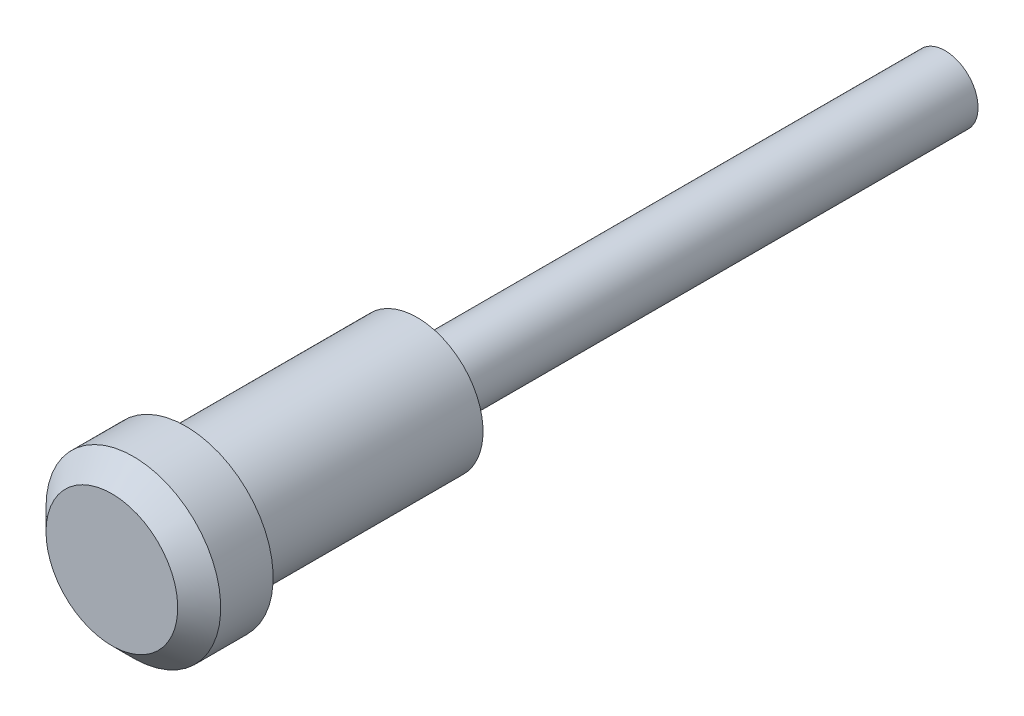
SolidWorks part; units mm, degrees
ref_plane "Front Plane" through (0, 0, 0) normal (0, 0, 1) x (1, 0, 0)
ref_plane "Top Plane" through (0, 0, 0) normal (0, 1, 0) x (1, 0, 0)
ref_plane "Right Plane" through (0, 0, 0) normal (1, 0, 0) x (0, 0, -1)
sketch "Sketch1" plane through (0, 0, 0) normal (1, 0, 0) x (0, 0, -1)
  line L0 (0, 0) -> (-25090.036, 0) construction
  line L1 (0, 6.35) -> (-22.3098, 6.35)
  line L2 (-22.3098, 6.35) -> (-22.3098, 8.4235)
  line L3 (-22.3098, 8.4235) -> (-27.3639, 8.4235)
  line L4 (-27.3639, 8.4235) -> (-29.4374, 6.35)
  line L5 (-29.4374, 6.35) -> (-29.4374, 0)
  line L6 (-29.4374, 0) -> (50.9037, 0)
  line L7 (50.9037, 0) -> (50.9037, 3.175)
  line L8 (50.9037, 3.175) -> (0, 3.175)
  line L9 (0, 3.175) -> (0, 6.35)
  point P5 (50.9037, 3.175)
  dimension "D1" = 6.35
revolve "Revolve1" add sketch "Sketch1" angle 360 about L0
